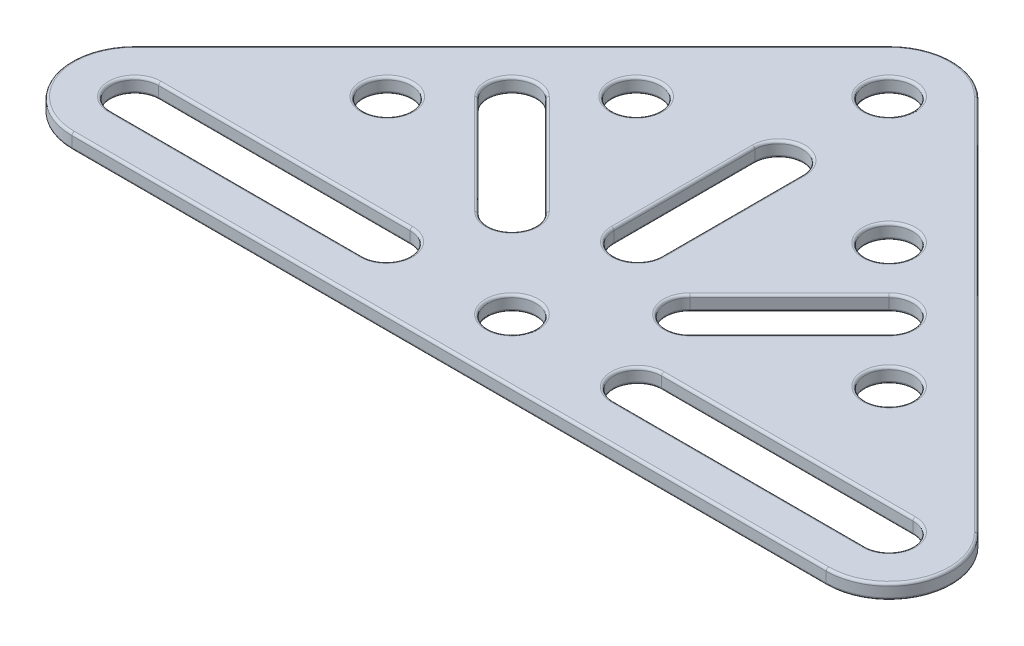
SolidWorks part; units mm, degrees
material "AISI 304"
ref_plane "Front" through (0, 0, 0) normal (0, 0, 1) x (1, 0, 0)
ref_plane "Top" through (0, 0, 0) normal (0, 1, 0) x (1, 0, 0)
ref_plane "Right" through (0, 0, 0) normal (1, 0, 0) x (0, 0, -1)
sketch "Sketch1" plane through (0, 0, 0) normal (0, 1, 0) x (1, 0, 0)
  line L0 (15.3303, 0) -> (91.5303, 0)
  line L1 (96.0204, 10.8401) -> (57.9204, 48.9401)
  line L2 (48.9401, 48.9401) -> (10.8401, 10.8401)
  arc A0 (57.9204, 48.9401) -> (48.9401, 48.9401) centre (53.4303, 44.45) ccw
  arc A1 (15.3303, 0) -> (10.8401, 10.8401) centre (15.3303, 6.35) cw
  arc A2 (91.5303, 0) -> (96.0204, 10.8401) centre (91.5303, 6.35) ccw
  circle A3 centre (53.4303, 44.45) radius 2.413
  circle A4 centre (53.4303, 6.35) radius 2.413
  point P9 (0, 0)
  dimension "D2" = 6.35
  dimension "D4" = 4.826
  dimension "D1" = 45
  dimension "D3" = 76.2
extrude "Extrude1" add sketch "Sketch1" along normal blind 1.524
sketch "Sketch2" plane through (0, 1.524, 0) normal (0, 1, 0) x (-1, 0, 0)
  line L0 (-48.9401, -48.9401) -> (-10.8401, -10.8401) construction
  line L2 (-74.1865, -23.6938) -> (-64.1286, -13.6359)
  line L4 (-70.774, -27.1062) -> (-60.7161, -17.0484)
  line L5 (-96.0204, -10.8401) -> (-57.9204, -48.9401) construction
  circle A1 centre (-53.4303, -6.35) radius 2.413 construction
  arc A3 (-60.7161, -17.0484) -> (-64.1286, -13.6359) centre (-62.4224, -15.3421) ccw
  arc A4 (-74.1865, -23.6938) -> (-70.774, -27.1062) centre (-72.4803, -25.4) ccw
  dimension "D3" = 6.35
  dimension "D4" = 2.413
  dimension "D1" = 4.826
  dimension "D2" = 14.224
extrude "Cut-Extrude1" cut sketch "Sketch2" against normal through all
pattern_circular "CirPattern1" count 3 over 90 about axis through (53.4303, 0, -6.35) along (0, 1, 0) of "Cut-Extrude1"
sketch "Sketch3" plane through (0, 1.524, 0) normal (0, 1, 0) x (-1, 0, 0)
  line L0 (-48.9401, -48.9401) -> (-10.8401, -10.8401) construction
  line L1 (-15.3303, -8.763) -> (-40.7303, -8.763)
  line L3 (-15.3303, -3.937) -> (-40.7303, -3.937)
  arc A0 (-15.3303, -8.763) -> (-15.3303, -3.937) centre (-15.3303, -6.35) ccw
  arc A1 (-10.8401, -10.8401) -> (-15.3303, 0) centre (-15.3303, -6.35) ccw construction
  arc A2 (-40.7303, -3.937) -> (-40.7303, -8.763) centre (-40.7303, -6.35) ccw
  circle A3 centre (-53.4303, -6.35) radius 2.413 construction
  circle A4 centre (-28.0822, -19.102) radius 2.413
  circle A5 centre (-40.6546, -31.6743) radius 2.413
  circle A6 centre (-53.4303, -44.45) radius 2.413 construction
  dimension "D1" = 4.826
  dimension "D2" = 12.7
  dimension "D6" = 6.35
  dimension "D3" = 18.034
  dimension "D4" = 35.814
  dimension "D5" = 6.35
extrude "Cut-Extrude2" cut sketch "Sketch3" against normal through all
ref_plane "Plane1" through (53.4303, 0, 0) normal (-1, 0, 0) x (0, 0, 1)
mirror "Mirror1" about plane through (53.4303, 0, 0) normal (-1, 0, 0) of "Cut-Extrude2"
fillet "Fillet1" radius 0.254 64 edges at (66.2059, 0, -29.2613) (78.8303, 0, -3.937) (63.7173, 0, -6.35) (78.8303, 0, -8.763) (93.9433, 0, -6.35) (40.6546, 0, -29.2613) (28.0822, 0, -16.689) (43.1433, 0, -6.35) (28.0303, 0, -3.937) (12.9173, 0, -6.35) (28.0303, 0, -8.763) (46.1444, 0, -13.6359) (37.703, 0, -18.6648) (32.674, 0, -27.1062) (41.1154, 0, -22.0773) (53.4303, 0, -16.6538) (51.0173, 0, -26.1788) (53.4303, 0, -35.7038) (55.8433, 0, -26.1788) (60.7161, 0, -13.6359) (65.7451, 0, -22.0773) (74.1865, 0, -27.1062) (69.1576, 0, -18.6648) (53.4303, 0, -42.037) (29.8901, 0, -29.8901) (9.4636, 0, -3.92) (53.4303, 0, 0) (97.3969, 0, -3.92) (76.9704, 0, -29.8901) (53.4303, 0, -50.8) (53.4303, 0, -3.937) (78.7783, 0, -16.689) (66.2059, 1.524, -29.2613) (63.7173, 1.524, -6.35) (78.8303, 1.524, -3.937) (93.9433, 1.524, -6.35) (78.8303, 1.524, -8.763) (40.6546, 1.524, -29.2613) (28.0822, 1.524, -16.689) (28.0303, 1.524, -3.937) (43.1433, 1.524, -6.35) (28.0303, 1.524, -8.763) (12.9173, 1.524, -6.35) (37.703, 1.524, -18.6648) (46.1444, 1.524, -13.6359) (41.1154, 1.524, -22.0773) (32.674, 1.524, -27.1062) (51.0173, 1.524, -26.1788) (53.4303, 1.524, -16.6538) (55.8433, 1.524, -26.1788) (53.4303, 1.524, -35.7038) (65.7451, 1.524, -22.0773) (60.7161, 1.524, -13.6359) (69.1576, 1.524, -18.6648) (74.1865, 1.524, -27.1062) (53.4303, 1.524, -42.037) (76.9704, 1.524, -29.8901) (97.3969, 1.524, -3.92) (53.4303, 1.524, 0) (9.4636, 1.524, -3.92) (29.8901, 1.524, -29.8901) (53.4303, 1.524, -50.8) (53.4303, 1.524, -3.937) (78.7783, 1.524, -16.689)
